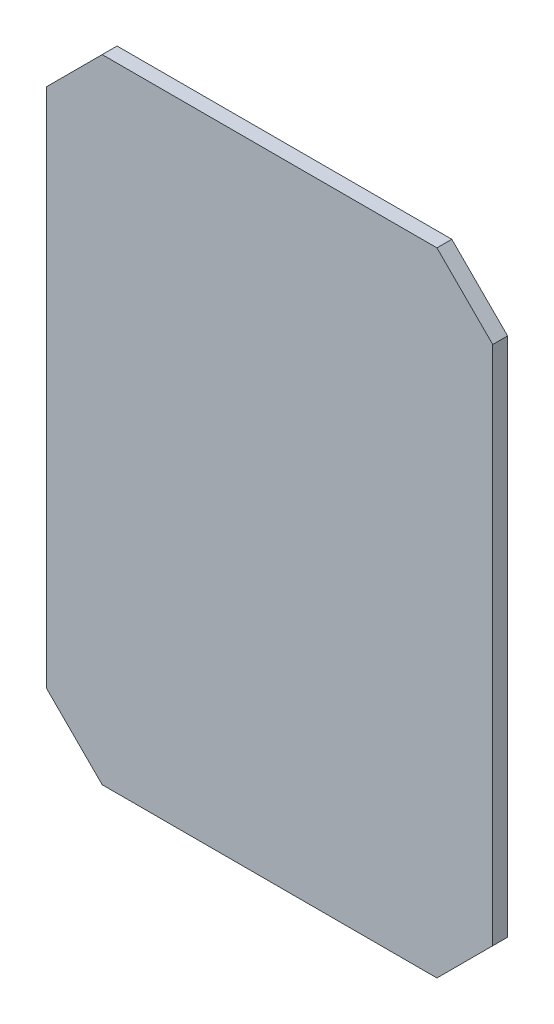
SolidWorks part; units mm, degrees
ref_plane "前视基准面" through (0, 0, 0) normal (0, 0, 1) x (1, 0, 0)
ref_plane "上视基准面" through (0, 0, 0) normal (0, 1, 0) x (1, 0, 0)
ref_plane "右视基准面" through (0, 0, 0) normal (1, 0, 0) x (0, 0, -1)
sketch "草图1" plane through (0, 0, 0) normal (0, 0, 1) x (1, 0, 0)
  line L0 (-95.9079, 78.0206) -> (-65.9079, 108.0206)
  line L1 (-65.9079, 108.0206) -> (114.0921, 108.0206)
  line L2 (-95.9079, 78.0206) -> (-95.9079, -201.9794)
  line L3 (-65.9079, -231.9794) -> (114.0921, -231.9794)
  line L4 (144.0921, 78.0206) -> (144.0921, -201.9794)
  line L5 (114.0921, 108.0206) -> (144.0921, 78.0206)
  line L6 (144.0921, -201.9794) -> (114.0921, -231.9794)
  line L7 (-95.9079, -201.9794) -> (-65.9079, -231.9794)
  point P0 (-95.9079, 108.0206)
  point P1 (144.0921, -231.9794)
  point P2 (-95.9079, -231.9794)
  point P3 (144.0921, 108.0206)
  dimension "D1" = 240
  dimension "D2" = 340
extrude "凸台-拉伸1" add sketch "草图1" along normal blind 8 contours L1 L5 L4 L6 L3 L7 L2 L0
sketch "草图2" plane through (0, 0, 0) normal (0, 0, 1) x (1, 0, 0)
  line L0 (144.0921, -61.9794) -> (-95.9079, -61.9794) construction
  line L1 (144.0921, 78.0206) -> (144.0921, -201.9794) construction
  line L2 (-95.9079, 78.0206) -> (-95.9079, -201.9794) construction
  line L3 (24.0921, 108.0206) -> (24.0921, -231.9794) construction
  line L4 (-65.9079, 108.0206) -> (114.0921, 108.0206) construction
  line L5 (-65.9079, -231.9794) -> (114.0921, -231.9794) construction
  point P12 (24.0921, -61.9794)
